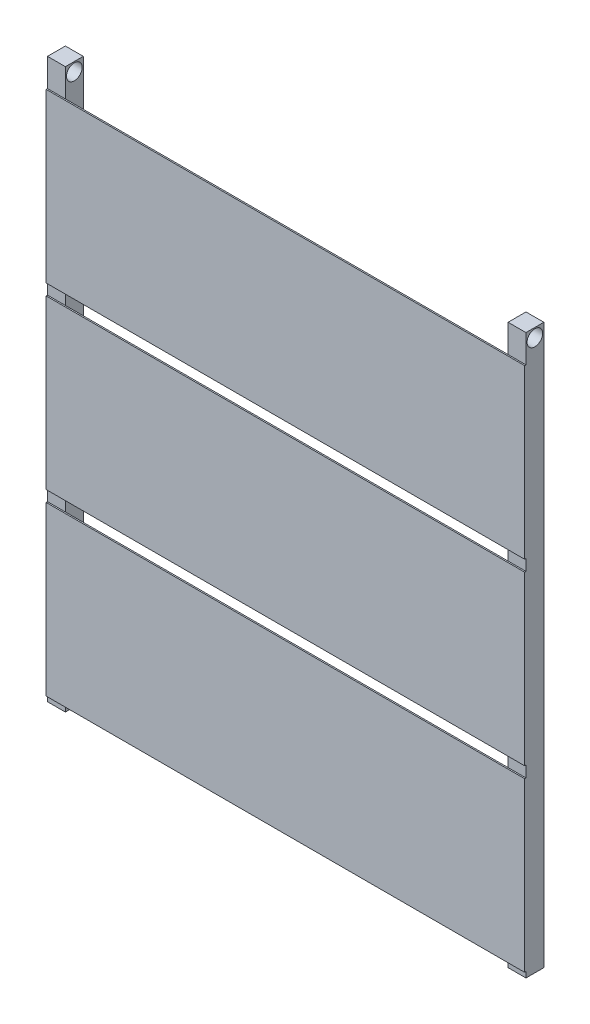
SolidWorks part; units mm, degrees
ref_plane "Front Plane" through (0, 0, 0) normal (0, 0, 1) x (1, 0, 0)
ref_plane "Top Plane" through (0, 0, 0) normal (0, 1, 0) x (1, 0, 0)
ref_plane "Right Plane" through (0, 0, 0) normal (1, 0, 0) x (0, 0, -1)
sketch "Sketch1" plane through (0, 0, 0) normal (0, 1, 0) x (1, 0, 0)
  line L0 (0, 151.6053) -> (0, -148.0359) construction
  line L1 (-214, -11.4545) -> (-198, -11.4545)
  line L2 (-214, -11.4545) -> (-214, 4.5455)
  line L3 (-214, 4.5455) -> (-198, 4.5455)
  line L4 (-198, -11.4545) -> (-198, 4.5455)
  line L5 (-214, -11.4545) -> (-198, 4.5455) construction
  line L6 (-214, 4.5455) -> (-198, -11.4545) construction
  line L7 (214, 4.5455) -> (198, -11.4545) construction
  line L8 (214, -11.4545) -> (198, 4.5455) construction
  line L9 (198, -11.4545) -> (198, 4.5455)
  line L10 (214, 4.5455) -> (198, 4.5455)
  line L11 (214, -11.4545) -> (214, 4.5455)
  line L12 (214, -11.4545) -> (198, -11.4545)
  point P0 (-206, -3.4545)
  point P12 (206, -3.4545)
  dimension "D1" = 16
  dimension "D2" = 16
  dimension "D3" = 206
extrude "Boss-Extrude1" add sketch "Sketch1" along normal mid plane 500
sketch "Sketch2" plane through (0, 0, 11.4545) normal (0, 0, 1) x (1, 0, 0)
  line L0 (214, 250) -> (214, -250) construction
  line L1 (-214, 75) -> (214, 75)
  line L2 (-214, 75) -> (-214, 225)
  line L3 (-214, 225) -> (214, 225)
  line L4 (214, 75) -> (214, 225)
  line L5 (-214, 75) -> (214, 225) construction
  line L6 (-214, 225) -> (214, 75) construction
  line L7 (-214, 250) -> (-198, 250) construction
  line L8 (-214, -85) -> (-214, 65)
  line L9 (-214, 65) -> (214, 65)
  line L10 (214, -85) -> (214, 65)
  line L11 (-214, -85) -> (214, -85)
  line L12 (-214, -245) -> (-214, -95)
  line L13 (-214, -95) -> (214, -95)
  line L14 (214, -245) -> (214, -95)
  line L15 (-214, -245) -> (214, -245)
  point P0 (0, 150)
  dimension "D1" = 25
  dimension "D2" = 428
  dimension "D3" = 150
  dimension "D4" = 3
extrude "Boss-Extrude2" add sketch "Sketch2" along normal blind 1.2
sketch "Sketch3" plane through (-198, 0, 0) normal (1, 0, 0) x (0, 0, -1)
  line L0 (-11.4545, 250) -> (4.5455, 250) construction
  circle A0 centre (-3.4545, 242) radius 7
  dimension "D1" = 14
  dimension "D2" = 8
extrude "Cut-Extrude1" cut sketch "Sketch3" along normal through all both and the other way through all
